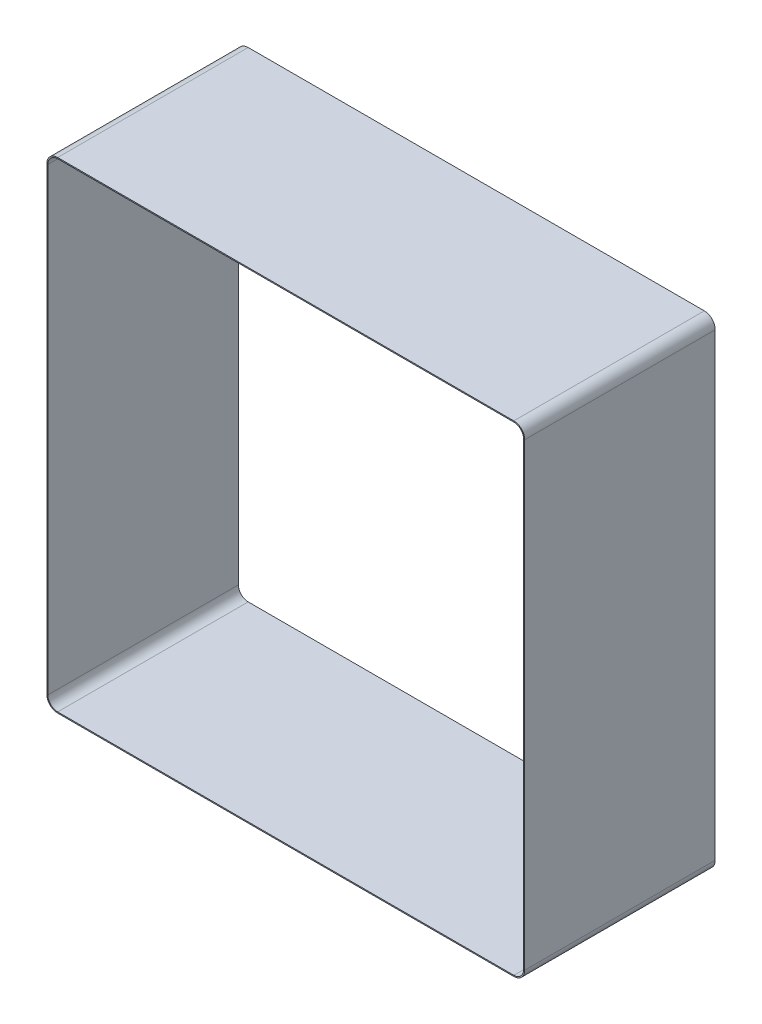
SolidWorks part; units mm, degrees
material "Pure Silver"
ref_plane "Front" through (0, 0, 0) normal (0, 0, 1) x (1, 0, 0)
ref_plane "Top" through (0, 0, 0) normal (0, 1, 0) x (1, 0, 0)
ref_plane "Right" through (0, 0, 0) normal (1, 0, 0) x (0, 0, -1)
sketch "Sketch1" plane through (0, 0, 0) normal (0, 0, 1) x (1, 0, 0)
  line L0 (-55.499, 53.594) -> (-55.499, -53.594)
  line L1 (-53.213, 56.134) -> (53.213, 56.134)
  line L2 (-55.753, 53.594) -> (-55.753, -53.594)
  line L3 (-53.213, -56.134) -> (53.213, -56.134)
  line L4 (55.753, 53.594) -> (55.753, -53.594)
  line L5 (-55.753, 56.134) -> (55.753, -56.134) construction
  line L6 (-55.753, -56.134) -> (55.753, 56.134) construction
  line L7 (-53.213, -55.88) -> (53.213, -55.88)
  line L8 (55.499, 53.594) -> (55.499, -53.594)
  line L9 (-53.213, 55.88) -> (53.213, 55.88)
  arc A0 (-55.753, -53.594) -> (-53.213, -56.134) centre (-53.213, -53.594) ccw
  arc A1 (55.753, -53.594) -> (53.213, -56.134) centre (53.213, -53.594) cw
  arc A2 (55.753, 53.594) -> (53.213, 56.134) centre (53.213, 53.594) ccw
  arc A3 (-53.213, 56.134) -> (-55.753, 53.594) centre (-53.213, 53.594) ccw
  arc A4 (-55.499, -53.594) -> (-53.213, -55.88) centre (-53.213, -53.594) ccw
  arc A5 (55.499, -53.594) -> (53.213, -55.88) centre (53.213, -53.594) cw
  arc A6 (55.499, 53.594) -> (53.213, 55.88) centre (53.213, 53.594) ccw
  arc A7 (-53.213, 55.88) -> (-55.499, 53.594) centre (-53.213, 53.594) ccw
  point P0 (0, 0)
  dimension "D3" = 2.54
  dimension "D1" = 111.506
  dimension "D2" = 112.268
  dimension "D4" = 0.254
extrude "Boss-Extrude1" add sketch "Sketch1" along normal blind 44.45
